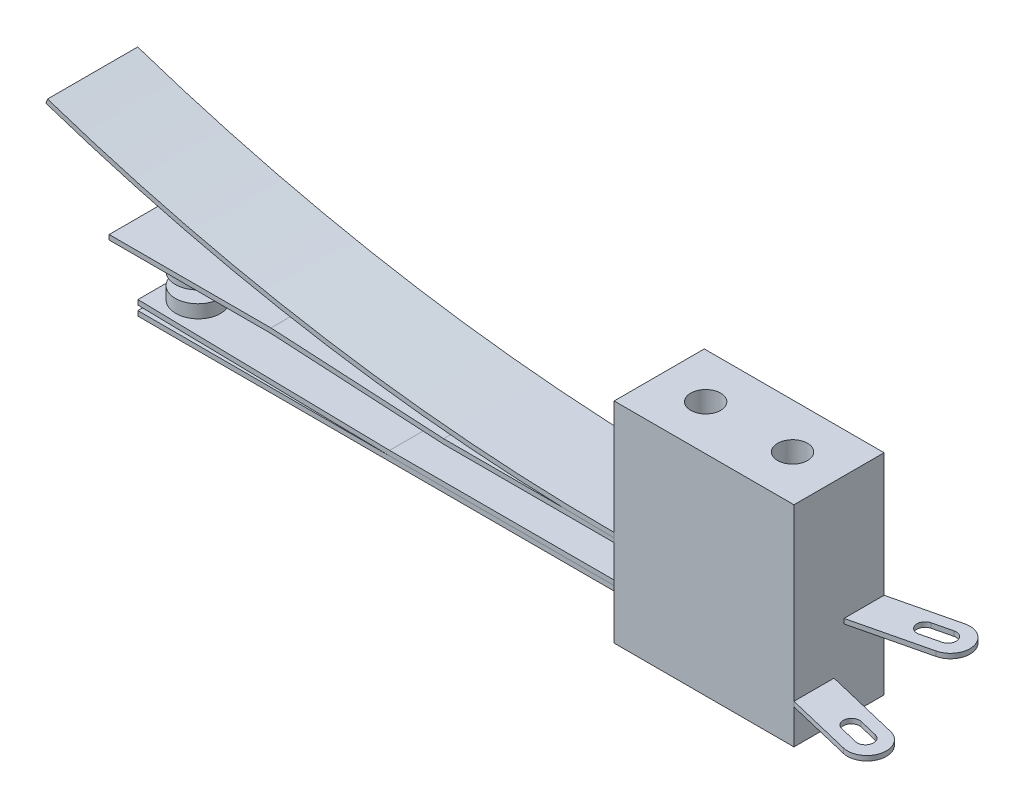
SolidWorks part; units mm, degrees
ref_plane "Front Plane" through (0, 0, 0) normal (0, 0, 1) x (1, 0, 0)
ref_plane "Top Plane" through (0, 0, 0) normal (0, 1, 0) x (1, 0, 0)
ref_plane "Right Plane" through (0, 0, 0) normal (1, 0, 0) x (0, 0, -1)
sketch "Sketch1" plane through (0, 0, 0) normal (0, 1, 0) x (1, 0, 0)
  line L1 (-9.525, -4.7752) -> (9.525, -4.7752)
  line L2 (-9.525, -4.7752) -> (-9.525, 4.7752)
  line L3 (-9.525, 4.7752) -> (9.525, 4.7752)
  line L4 (9.525, -4.7752) -> (9.525, 4.7752)
  line L5 (-9.525, -4.7752) -> (9.525, 4.7752) construction
  line L6 (-9.525, 4.7752) -> (9.525, -4.7752) construction
  point P0 (0, 0)
  dimension "D1" = 9.5504
  dimension "D2" = 19.05
extrude "Boss-Extrude1" add sketch "Sketch1" along normal mid plane 22.225
ref_plane "Plane1" through (0, -7.9375, 0) normal (0, -1, 0) x (-1, 0, 0)
sketch "Sketch2" plane through (0, -7.9375, 0) normal (0, -1, 0) x (-1, 0, 0)
  line L0 (9.525, 4.7752) -> (9.525, -4.7752) construction
  line L1 (9.525, -3.175) -> (61.595, -3.175)
  line L2 (9.525, -3.175) -> (9.525, 3.175)
  line L3 (9.525, 3.175) -> (61.595, 3.175)
  line L4 (61.595, -3.175) -> (61.595, 3.175)
  point P6 (9.525, 0)
  point P7 (9.525, 0)
  dimension "D1" = 6.35
  dimension "D2" = 52.07
extrude "Boss-Extrude2" add sketch "Sketch2" against normal blind 0.508
sketch "Sketch3" plane through (0, 0, 0) normal (0, 0, 1) x (1, 0, 0)
  line L0 (-9.525, -7.4295) -> (-34.925, -7.4295)
  line L1 (-9.525, -7.4295) -> (-61.595, -7.4295) construction
  line L2 (-34.925, -7.4295) -> (-61.595, -6.9215)
  line L3 (-61.595, -6.9215) -> (-61.5853, -6.4136)
  line L4 (-61.5853, -6.4136) -> (-34.9202, -6.9215)
  line L5 (-34.9202, -6.9215) -> (-9.525, -6.9215)
  line L6 (-9.525, 11.1125) -> (-9.525, -11.1125) construction
  line L7 (-9.525, -6.9215) -> (-9.525, -7.4295)
  line L8 (-9.525, -7.4295) -> (-9.525, -7.9375) construction
  point P13 (0, 0)
  dimension "D1" = 25.4
  dimension "D2" = 0.508
extrude "Boss-Extrude3" add sketch "Sketch3" along normal mid plane 6.35 separate body
ref_plane "Plane2" through (0, -2.4765, 0) normal (0, -1, 0) x (-1, 0, 0)
sketch "Sketch4" plane through (0, -2.4765, 0) normal (0, -1, 0) x (-1, 0, 0)
  line L0 (9.525, -3.175) -> (9.525, 3.175) construction
  line L1 (9.525, 3.175) -> (61.5853, 3.175)
  line L2 (9.525, 3.175) -> (9.525, -3.175)
  line L3 (9.525, -3.175) -> (61.5853, -3.175)
  line L4 (61.5853, 3.175) -> (61.5853, -3.175)
  line L5 (61.5853, -3.175) -> (61.5853, 3.175) construction
  point P4 (9.525, 0)
  dimension "D1" = 6.35
extrude "Boss-Extrude4" add sketch "Sketch4" against normal blind 0.508
sketch "Sketch5" plane through (0, 0, 0) normal (0, 0, 1) x (1, 0, 0)
  line L0 (-9.525, -1.9685) -> (-27.686, -1.9685)
  line L1 (-9.525, -1.9685) -> (-61.5853, -1.9685) construction
  line L2 (-27.686, -1.9685) -> (-45.9784, -0.9525)
  line L3 (-45.9784, -0.9525) -> (-63.1093, -0.9525)
  line L4 (-63.1093, -0.9525) -> (-63.1093, -0.4445)
  line L5 (-63.1093, -0.4445) -> (-45.9643, -0.4445)
  line L6 (-45.9643, -0.4445) -> (-27.6719, -1.4605)
  line L7 (-27.6719, -1.4605) -> (-9.525, -1.4605)
  line L8 (-9.525, 11.1125) -> (-9.525, -11.1125) construction
  line L9 (-9.525, -1.4605) -> (-9.525, -1.9685)
  line L10 (-9.525, -7.4295) -> (-9.525, -6.9215) construction
  line L11 (-61.5853, -1.9685) -> (-61.5853, -2.4765) construction
  line L12 (-36.8181, -0.9525) -> (-36.8463, -1.4597) construction
  dimension "D1" = 1.524
  dimension "D2" = 1.016
  dimension "D3" = 18.161
  dimension "D4" = 17.145
extrude "Boss-Extrude5" add sketch "Sketch5" along normal mid plane 9.398 separate body
sketch "Sketch6" plane through (0, 0, 0) normal (0, 0, 1) x (1, 0, 0)
  line L0 (-9.525, -1.4605) -> (-27.6719, -1.4605) construction
  line L1 (-9.525, 11.1125) -> (-9.525, -11.1125) construction
  line L2 (-9.525, 11.1125) -> (9.525, 11.1125) construction
  line L3 (-39.9371, 1.5016) -> (-40.0186, 1.0002) construction
  line L4 (-9.525, -1.4605) -> (-9.525, -0.9525)
  line L5 (-9.525, -7.4295) -> (-9.525, -6.9215) construction
  line L6 (-39.6864, 1.4609) -> (-40.1878, 1.5423) construction
  line L7 (-69.723, 8.3185) -> (-69.5622, 8.8004)
  line L8 (-69.723, 8.3185) -> (-70.2049, 8.4793) construction
  arc A0 (-9.525, -1.4605) -> (-69.723, 8.3185) centre (-9.525, 188.7138) cw
  arc A1 (-69.5622, 8.8004) -> (-9.525, -0.9525) centre (-9.525, 188.7138) ccw
  point P20 (-39.9371, 1.5016)
  dimension "D1" = 60.198
  dimension "D2" = 2.794
extrude "Boss-Extrude6" add sketch "Sketch6" along normal mid plane 9.5504 separate body
sketch "Sketch7" plane through (0, -2.4765, 0) normal (0, -1, 0) x (1, 0, 0)
  line L0 (-61.5853, 3.175) -> (-61.5853, -3.175) construction
  circle A0 centre (-58.4103, 0) radius 2.3812
  point P4 (-61.5853, 0)
  point P5 (-56.824, 0)
  dimension "D1" = 4.7625
  dimension "D2" = 3.175
extrude "Boss-Extrude7" add sketch "Sketch7" along normal blind 1.3716
sketch "Sketch8" plane through (0, -3.8481, 0) normal (0, -1, 0) x (1, 0, 0)
  circle A1 centre (-58.4103, 0) radius 2.3813
  circle A2 centre (-58.4103, 0) radius 2.3812
  dimension "D1" = 0
extrude "Boss-Extrude8" add sketch "Sketch8" along normal up to surface (1.356 mm away) from offset 1.27
sketch "Sketch9" plane through (0, -1.9685, 0) normal (0, 1, 0) x (1, 0, 0)
  circle A0 centre (-58.4103, 0) radius 1.27
  circle A1 centre (-58.4103, 0) radius 2.3812 construction
  dimension "D1" = 2.54
extrude "Boss-Extrude9" add sketch "Sketch9" along normal blind 0.508
sketch "Sketch10" plane through (0, -7.4295, 0) normal (0, 1, 0) x (1, 0, 0)
  circle A0 centre (-58.4103, 0) radius 1.27 construction
  circle A1 centre (-58.4103, 0) radius 1.27
extrude "Boss-Extrude10" add sketch "Sketch10" along normal up to surface (0.4473 mm away)
sketch "Sketch11" plane through (0, -6.9215, 0) normal (0, 1, 0) x (1, 0, 0)
  line L0 (9.525, -4.7752) -> (16.4282, -6.4327)
  line L1 (9.525, -4.7752) -> (9.525, -0.5304)
  line L2 (9.525, -4.7752) -> (9.525, 4.7752) construction
  line L3 (9.525, -0.5304) -> (17.3919, -2.4192)
  line L4 (17.3919, -2.4192) -> (16.4282, -6.4327) construction
  line L5 (18.9168, -4.9078) -> (9.525, -2.6528) construction
  line L6 (16.91, -6.4897) -> (9.525, -6.4897) construction
  line L7 (9.525, -6.4897) -> (9.525, -4.7752) construction
  line L8 (18.9738, -4.426) -> (18.9738, -0.5304) construction
  line L9 (18.9738, -0.5304) -> (9.525, -0.5304) construction
  line L10 (14.9444, -3.0659) -> (16.8956, -3.5343)
  line L11 (16.8956, -3.5343) -> (16.4923, -5.2138) construction
  line L12 (16.4923, -5.2138) -> (14.5412, -4.7453)
  line L13 (14.5412, -4.7453) -> (14.9444, -3.0659) construction
  line L14 (9.525, 0) -> (0, 0) construction
  line L15 (14.5412, 4.7453) -> (14.9444, 3.0659) construction
  line L16 (16.8956, 3.5343) -> (16.4923, 5.2138) construction
  line L17 (18.9738, 0.5304) -> (9.525, 0.5304) construction
  line L18 (18.9738, 4.426) -> (18.9738, 0.5304) construction
  line L19 (9.525, 6.4897) -> (9.525, 4.7752) construction
  line L20 (16.91, 6.4897) -> (9.525, 6.4897) construction
  line L21 (18.9168, 4.9078) -> (9.525, 2.6528) construction
  line L22 (17.3919, 2.4192) -> (16.4282, 6.4327) construction
  line L23 (16.4923, 5.2138) -> (14.5412, 4.7453) construction
  line L24 (14.9444, 3.0659) -> (16.8956, 3.5343) construction
  line L25 (9.525, 0.5304) -> (17.3919, 2.4192) construction
  line L26 (9.525, 4.7752) -> (9.525, 0.5304) construction
  line L27 (9.525, 4.7752) -> (16.4282, 6.4327) construction
  arc A0 (17.3919, -2.4192) -> (16.4282, -6.4327) centre (16.91, -4.426) cw
  arc A1 (14.9444, -3.0659) -> (14.5412, -4.7453) centre (14.7428, -3.9056) ccw
  arc A2 (16.8956, -3.5343) -> (16.4923, -5.2138) centre (16.6939, -4.3741) cw
  arc A3 (16.8956, 3.5343) -> (16.4923, 5.2138) centre (16.6939, 4.3741) ccw construction
  arc A4 (14.9444, 3.0659) -> (14.5412, 4.7453) centre (14.7428, 3.9056) cw construction
  arc A5 (17.3919, 2.4192) -> (16.4282, 6.4327) centre (16.91, 4.426) ccw construction
  point P20 (13.9031, -3.704)
  point P21 (17.5337, -4.5757)
  dimension "D1" = 1.7145
  dimension "D2" = 9.4488
  dimension "D3" = 4.1275
  dimension "D4" = 3.7338
  dimension "D5" = 1.7272
  dimension "D6" = 1.4224
extrude "Boss-Extrude11" add sketch "Sketch11" against normal blind 0.508
sketch "Sketch12" plane through (0, -2.4765, 0) normal (0, -1, 0) x (1, 0, 0)
  line L0 (14.9444, -3.0659) -> (16.8956, -3.5343) construction
  line L1 (16.4923, -5.2138) -> (14.5412, -4.7453) construction
  line L2 (9.525, -4.7752) -> (16.4282, -6.4327) construction
  line L3 (9.525, -4.7752) -> (9.525, -0.5304) construction
  line L4 (9.525, -0.5304) -> (17.3919, -2.4192) construction
  line L5 (14.9444, -3.0659) -> (16.8956, -3.5343)
  line L6 (16.4923, -5.2138) -> (14.5412, -4.7453)
  line L7 (9.525, -4.7752) -> (16.4282, -6.4327)
  line L8 (9.525, -4.7752) -> (9.525, -0.5304)
  line L9 (9.525, -0.5304) -> (17.3919, -2.4192)
  arc A0 (16.4923, -5.2138) -> (16.8956, -3.5343) centre (16.6939, -4.3741) ccw construction
  arc A1 (14.9444, -3.0659) -> (14.5412, -4.7453) centre (14.7428, -3.9056) ccw construction
  arc A2 (16.4282, -6.4327) -> (17.3919, -2.4192) centre (16.91, -4.426) ccw construction
  arc A3 (16.4923, -5.2138) -> (16.8956, -3.5343) centre (16.6939, -4.3741) ccw
  arc A4 (14.9444, -3.0659) -> (14.5412, -4.7453) centre (14.7428, -3.9056) ccw
  arc A5 (16.4282, -6.4327) -> (17.3919, -2.4192) centre (16.91, -4.426) ccw
extrude "Boss-Extrude12" add sketch "Sketch12" against normal blind 0.508
sketch "Sketch13" plane through (0, 11.1125, 0) normal (0, 1, 0) x (1, 0, 0)
  line L0 (0, 4.7752) -> (0, -4.7752) construction
  line L1 (9.525, 4.7752) -> (-9.525, 4.7752) construction
  line L2 (-9.525, -4.7752) -> (9.525, -4.7752) construction
  circle A0 centre (-4.6037, 0) radius 1.5875
  circle A1 centre (4.6037, 0) radius 1.5875
  point P4 (0, 0)
  point P12 (-4.6037, 0)
  dimension "D2" = 3.175
  dimension "D1" = 9.2075
extrude "Cut-Extrude1" cut sketch "Sketch13" against normal through all
